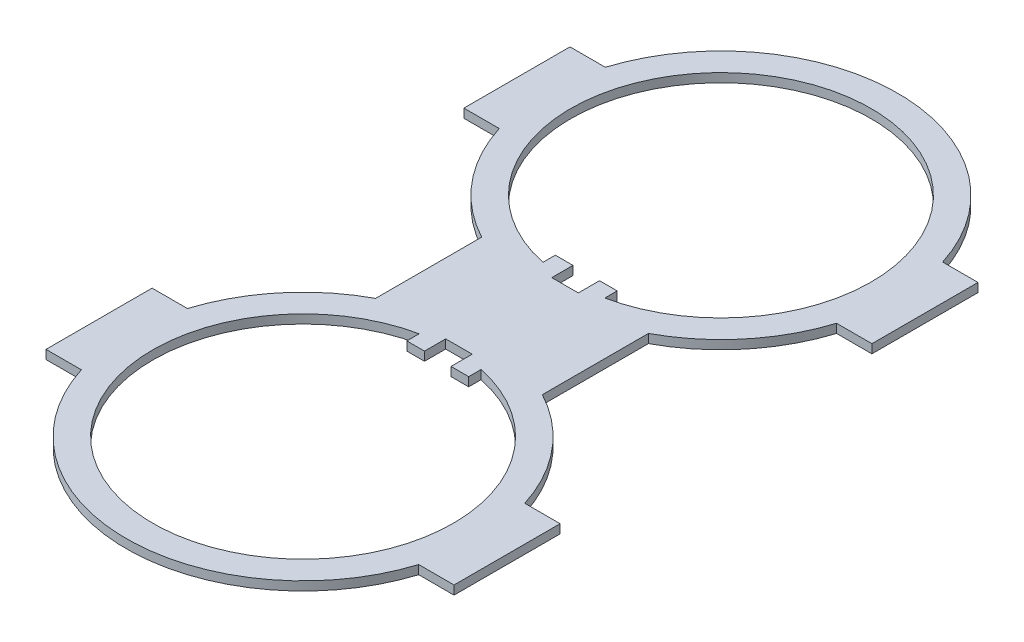
SolidWorks part; units mm, degrees
ref_plane "Front Plane" through (0, 0, 0) normal (0, 0, 1) x (1, 0, 0)
ref_plane "Top Plane" through (0, 0, 0) normal (0, 1, 0) x (1, 0, 0)
ref_plane "Right Plane" through (0, 0, 0) normal (1, 0, 0) x (0, 0, -1)
sketch "Sketch1" plane through (0, 0, 0) normal (0, 1, 0) x (1, 0, 0)
  line L0 (0, 0) -> (19.05, 0)
  line L1 (19.05, 0) -> (19.05, 15.24)
  line L2 (19.05, 15.24) -> (31.75, 15.24)
  line L3 (31.75, 15.24) -> (31.75, 6.35)
  line L4 (0, 0) -> (0, 15.24)
  line L5 (0, 15.24) -> (-12.7, 15.24)
  line L6 (-12.7, 15.24) -> (-12.7, 6.35)
  line L7 (130.6753, 150.0874) -> (156.0753, 150.0874)
  line L8 (156.0753, 150.0874) -> (156.0753, 73.8874)
  line L9 (156.0753, 73.8874) -> (130.6753, 73.8874)
  line L10 (-111.6253, 150.0874) -> (-137.0253, 150.0874)
  line L11 (-137.0253, 150.0874) -> (-137.0253, 73.8874)
  line L12 (-137.0253, 73.8874) -> (-111.6253, 73.8874)
  line L13 (-50.3735, 0) -> (-50.3735, -76.2)
  line L14 (69.4235, 0) -> (69.4235, -76.2)
  line L15 (0, -76.2) -> (19.05, -76.2)
  line L16 (19.05, -76.2) -> (19.05, -91.44)
  line L17 (19.05, -91.44) -> (31.75, -91.44)
  line L18 (31.75, -91.44) -> (31.75, -82.55)
  line L19 (0, -76.2) -> (0, -91.44)
  line L20 (0, -91.44) -> (-12.7, -91.44)
  line L21 (-12.7, -91.44) -> (-12.7, -82.55)
  line L22 (-111.6253, -150.0874) -> (-137.0253, -150.0874)
  line L23 (-137.0253, -150.0874) -> (-137.0253, -226.2874)
  line L24 (-137.0253, -226.2874) -> (-111.6253, -226.2874)
  line L25 (130.6753, -150.0874) -> (156.0753, -150.0874)
  line L26 (156.0753, -150.0874) -> (156.0753, -226.2874)
  line L27 (156.0753, -226.2874) -> (130.6753, -226.2874)
  line L28 (11.2022, 0) -> (11.2022, -76.2) construction
  arc A0 (-12.7, 6.35) -> (31.75, 6.35) centre (9.525, 111.9874) cw
  arc A1 (-111.6253, 150.0874) -> (130.6753, 150.0874) centre (9.525, 111.9874) cw
  arc A2 (-111.6253, 73.8874) -> (-50.3735, 0) centre (9.525, 111.9874) ccw
  arc A3 (130.6753, 73.8874) -> (69.4235, 0) centre (9.525, 111.9874) cw
  arc A4 (-12.7, -82.55) -> (31.75, -82.55) centre (9.525, -188.1874) ccw
  arc A5 (-50.3735, -76.2) -> (-111.6253, -150.0874) centre (9.525, -188.1874) ccw
  arc A6 (69.4235, -76.2) -> (130.6753, -150.0874) centre (9.525, -188.1874) cw
  arc A7 (130.6753, -226.2874) -> (-111.6253, -226.2874) centre (9.525, -188.1874) cw
  dimension "D5" = 25.4
  dimension "D7" = 127
  dimension "D8" = 127
  dimension "D9" = 107.95
  dimension "D10" = 76.2
  dimension "D11" = 107.95
  dimension "D12" = 76.2
  dimension "D13" = 127
  dimension "D1" = 19.05
  dimension "D2" = 15.24
  dimension "D3" = 12.7
  dimension "D4" = 8.89
  dimension "D6" = 76.2
extrude "Boss-Extrude1" add sketch "Sketch1" along normal blind 6.35
